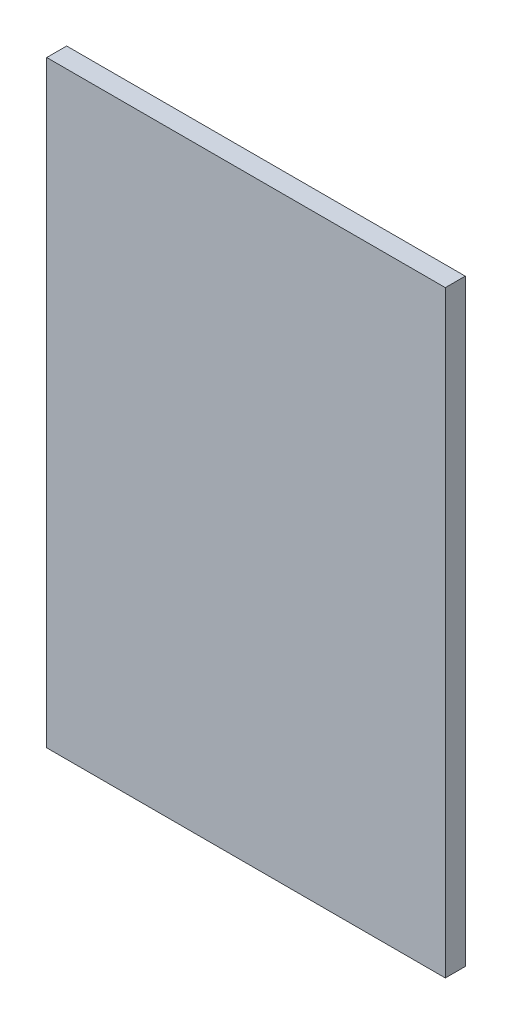
SolidWorks part; units mm, degrees
material "轻木"
ref_plane "前视基准面" through (0, 0, 0) normal (0, 0, 1) x (1, 0, 0)
ref_plane "上视基准面" through (0, 0, 0) normal (0, 1, 0) x (1, 0, 0)
ref_plane "右视基准面" through (0, 0, 0) normal (1, 0, 0) x (0, 0, -1)
sketch "Sketch1" plane through (0, 0, 0) normal (0, 0, 1) x (1, 0, 0)
  line L1 (-100, 150) -> (100, 150)
  line L2 (-100, 150) -> (-100, -150)
  line L3 (-100, -150) -> (100, -150)
  line L4 (100, 150) -> (100, -150)
  dimension "D1" = 100
  dimension "D2" = 100
  dimension "D3" = 150
  dimension "D4" = 150
extrude "Extrude1" add sketch "Sketch1" along normal blind 10
